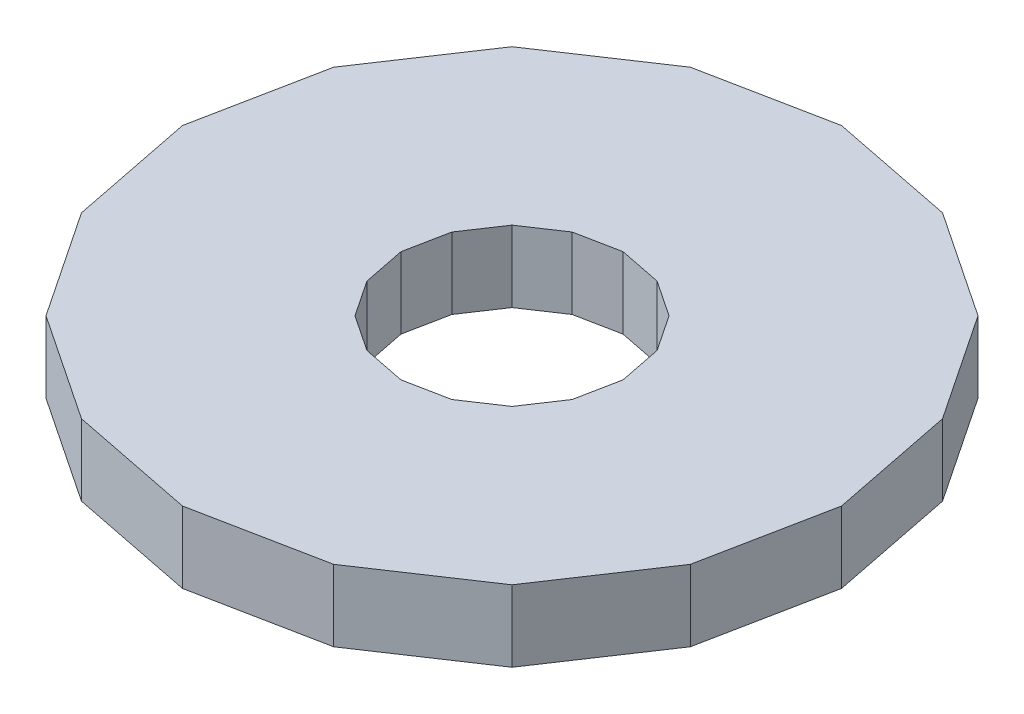
SolidWorks part; units mm, degrees
ref_plane "Front Plane" through (0, 0, 0) normal (0, 0, 1) x (1, 0, 0)
ref_plane "Top Plane" through (0, 0, 0) normal (0, 1, 0) x (1, 0, 0)
ref_plane "Right Plane" through (0, 0, 0) normal (1, 0, 0) x (0, 0, -1)
sketch "Sketch1" plane through (0, 0, 0) normal (0, 1, 0) x (1, 0, 0)
  line L1 (29.6127, 0) -> (27.3586, 11.3323)
  line L2 (27.3586, 11.3323) -> (20.9394, 20.9394)
  line L3 (20.9394, 20.9394) -> (11.3323, 27.3586)
  line L4 (11.3323, 27.3586) -> (0, 29.6127)
  line L5 (0, 29.6127) -> (-11.3323, 27.3586)
  line L6 (-11.3323, 27.3586) -> (-20.9394, 20.9394)
  line L7 (-20.9394, 20.9394) -> (-27.3586, 11.3323)
  line L8 (-27.3586, 11.3323) -> (-29.6127, 0)
  line L9 (-29.6127, 0) -> (-27.3586, -11.3323)
  line L10 (-27.3586, -11.3323) -> (-20.9394, -20.9394)
  line L11 (-20.9394, -20.9394) -> (-11.3323, -27.3586)
  line L12 (-11.3323, -27.3586) -> (0, -29.6127)
  line L13 (0, -29.6127) -> (11.3323, -27.3586)
  line L14 (11.3323, -27.3586) -> (20.9394, -20.9394)
  line L15 (20.9394, -20.9394) -> (27.3586, -11.3323)
  line L16 (27.3586, -11.3323) -> (29.6127, 0)
  line L17 (87.8824, 0) -> (81.1927, 33.6311)
  line L18 (81.1927, 33.6311) -> (62.1422, 62.1422)
  line L19 (62.1422, 62.1422) -> (33.6311, 81.1927)
  line L20 (33.6311, 81.1927) -> (0, 87.8824)
  line L21 (0, 87.8824) -> (-33.6311, 81.1927)
  line L22 (-33.6311, 81.1927) -> (-62.1422, 62.1422)
  line L23 (-62.1422, 62.1422) -> (-81.1927, 33.6311)
  line L24 (-81.1927, 33.6311) -> (-87.8824, 0)
  line L25 (-87.8824, 0) -> (-81.1927, -33.6311)
  line L26 (-81.1927, -33.6311) -> (-62.1422, -62.1422)
  line L27 (-62.1422, -62.1422) -> (-33.6311, -81.1927)
  line L28 (-33.6311, -81.1927) -> (0, -87.8824)
  line L29 (0, -87.8824) -> (33.6311, -81.1927)
  line L30 (33.6311, -81.1927) -> (62.1422, -62.1422)
  line L31 (62.1422, -62.1422) -> (81.1927, -33.6311)
  line L32 (81.1927, -33.6311) -> (87.8824, 0)
  circle A0 centre (0, 0) radius 29.0437 construction
  circle A1 centre (0, 0) radius 86.1937 construction
  dimension "D1" = 34.29
  dimension "D2" = 57.15
extrude "Boss-Extrude1" add sketch "Sketch1" along normal blind 19.05
